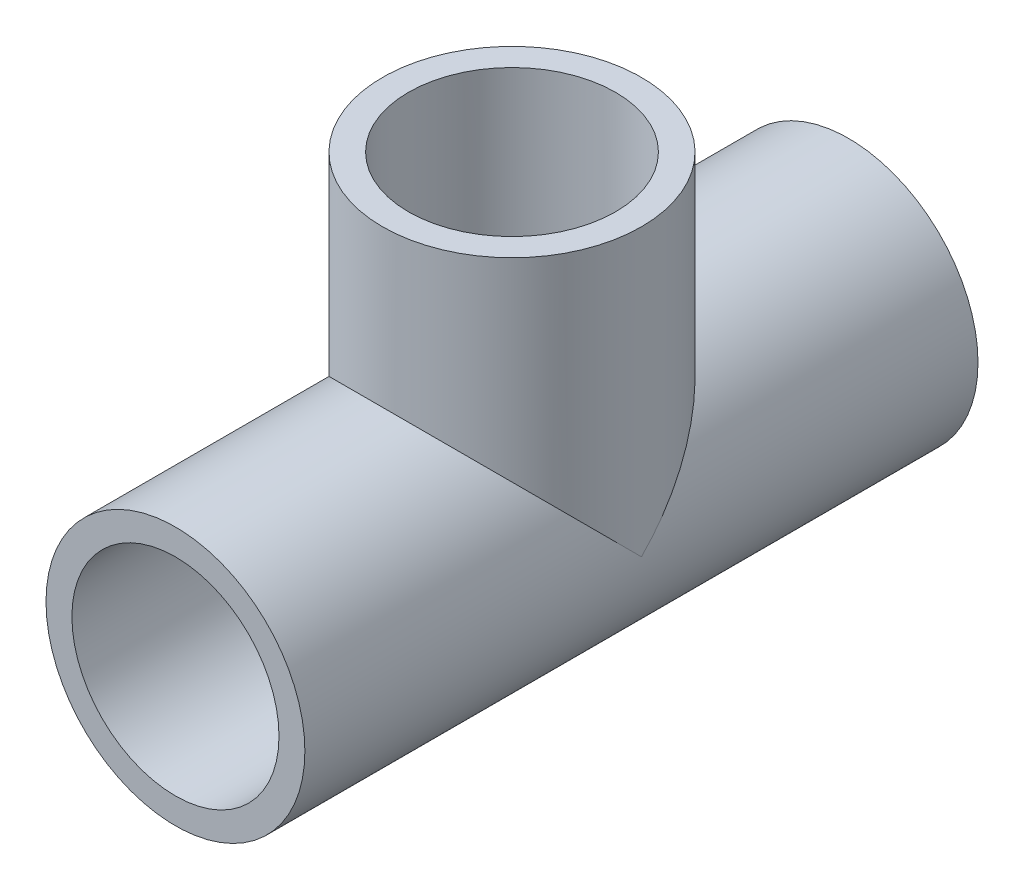
SolidWorks part; units mm, degrees
ref_plane "Front Plane" through (0, 0, 0) normal (0, 0, 1) x (1, 0, 0)
ref_plane "Top Plane" through (0, 0, 0) normal (0, 1, 0) x (1, 0, 0)
ref_plane "Right Plane" through (0, 0, 0) normal (1, 0, 0) x (0, 0, -1)
sketch "Sketch1" plane through (0, 0, 0) normal (0, 0, 1) x (1, 0, 0)
  circle A0 centre (0, 0) radius 15.875
  circle A1 centre (0, 0) radius 12.7
  dimension "D1" = 25.4
extrude "Boss-Extrude1" add sketch "Sketch1" along normal blind 82.55
sketch "Sketch2" plane through (0, 0, 0) normal (0, 1, 0) x (1, 0, 0)
  line L0 (0, 0) -> (0, -82.55)
  line L1 (-15.875, -82.55) -> (15.875, -82.55) construction
  circle A0 centre (0, -41.275) radius 12.7
  circle A1 centre (0, -41.275) radius 15.875
  dimension "D1" = 25.4
extrude "Boss-Extrude2" add sketch "Sketch2" along normal blind 35.052 contours A0 | A1
